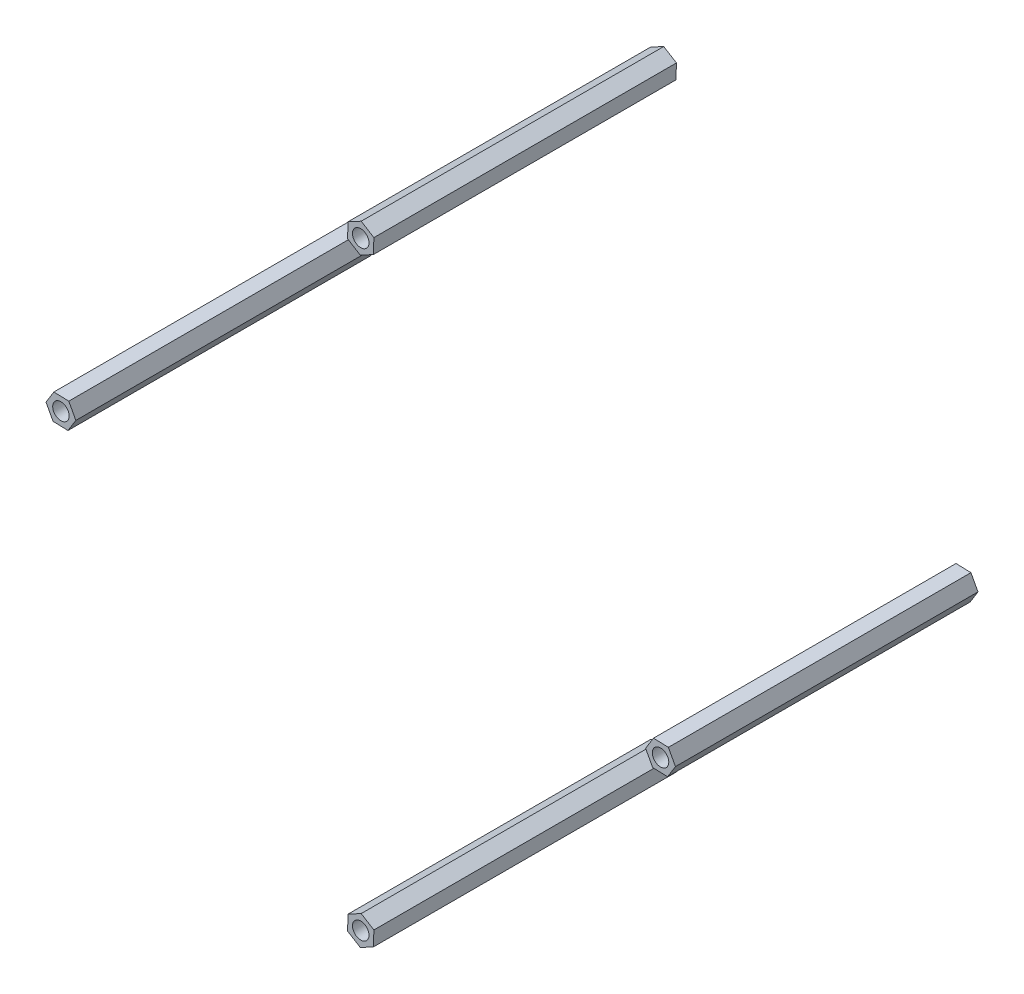
SolidWorks part; units mm, degrees
ref_plane "前视基准面" through (0, 0, 0) normal (0, 0, 1) x (1, 0, 0)
ref_plane "上视基准面" through (0, 0, 0) normal (0, 1, 0) x (1, 0, 0)
ref_plane "右视基准面" through (0, 0, 0) normal (1, 0, 0) x (0, 0, -1)
sketch "草图1" plane through (0, 0, 0) normal (0, 0, 1) x (1, 0, 0)
  line L0 (53.0711, -56.8069) -> (55.7834, -56.8909)
  line L1 (2.3069, -1.4289) -> (2.3909, 1.2834)
  line L2 (2.3909, 1.2834) -> (0.084, 2.7122)
  line L3 (0.084, 2.7122) -> (-2.3069, 1.4289)
  line L4 (-2.3069, 1.4289) -> (-2.3909, -1.2834)
  line L5 (-2.3909, -1.2834) -> (-0.084, -2.7122)
  line L6 (-0.084, -2.7122) -> (2.3069, -1.4289)
  line L7 (55.7834, -56.8909) -> (57.2122, -54.584)
  line L8 (57.2122, -54.584) -> (55.9289, -52.1931)
  line L9 (55.9289, -52.1931) -> (53.2166, -52.1091)
  line L10 (53.2166, -52.1091) -> (51.7878, -54.416)
  line L11 (51.7878, -54.416) -> (53.0711, -56.8069)
  line L12 (-2.3069, -107.5711) -> (-2.3909, -110.2834)
  line L13 (-2.3909, -110.2834) -> (-0.084, -111.7122)
  line L14 (-0.084, -111.7122) -> (2.3069, -110.4289)
  line L15 (2.3069, -110.4289) -> (2.3909, -107.7166)
  line L16 (2.3909, -107.7166) -> (0.084, -106.2878)
  line L17 (0.084, -106.2878) -> (-2.3069, -107.5711)
  line L18 (-53.0711, -52.1931) -> (-55.7834, -52.1091)
  line L19 (-55.7834, -52.1091) -> (-57.2122, -54.416)
  line L20 (-57.2122, -54.416) -> (-55.9289, -56.8069)
  line L21 (-55.9289, -56.8069) -> (-53.2166, -56.8909)
  line L22 (-53.2166, -56.8909) -> (-51.7878, -54.584)
  line L23 (-51.7878, -54.584) -> (-53.0711, -52.1931)
  circle A0 centre (0, 0) radius 2.35 construction
  circle A1 centre (0, 0) radius 1.5
  circle A2 centre (0, -54.5) radius 15 construction
  circle A3 centre (54.5, -54.5) radius 1.5
  circle A4 centre (0, -109) radius 1.5
  circle A5 centre (-54.5, -54.5) radius 1.5
  point P39 (0, -54.5)
  dimension "D1" = 4
extrude "凸台-拉伸1" add sketch "草图1" along normal blind 55
